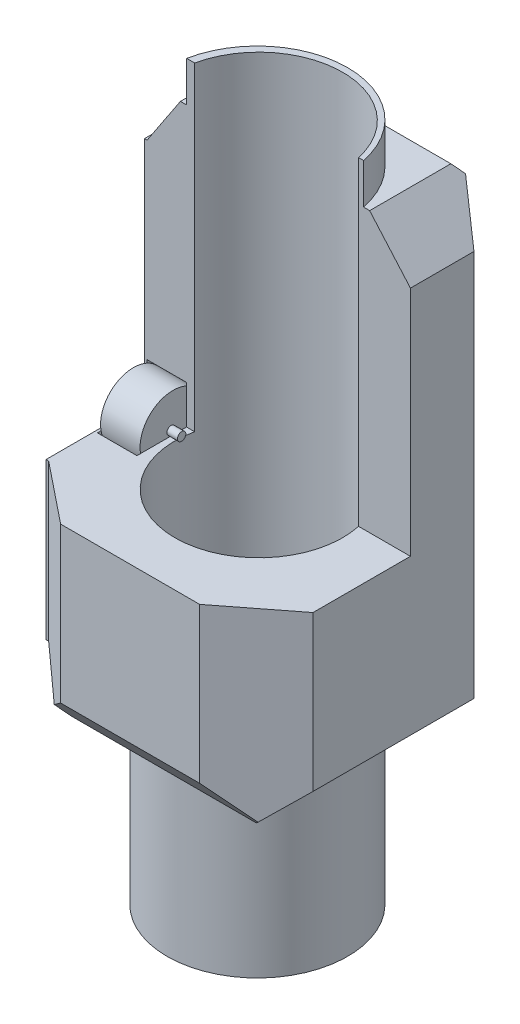
SolidWorks part; units mm, degrees
ref_plane "Front Plane" through (0, 0, 0) normal (0, 0, 1) x (1, 0, 0)
ref_plane "Top Plane" through (0, 0, 0) normal (0, 1, 0) x (1, 0, 0)
ref_plane "Right Plane" through (0, 0, 0) normal (1, 0, 0) x (0, 0, -1)
sketch "Sketch1" plane through (0, 0, 0) normal (0, 1, 0) x (1, 0, 0)
  line L1 (0, 0) -> (-100, 0)
  line L2 (0, 0) -> (0, 100)
  line L3 (0, 100) -> (-100, 100)
  line L4 (-100, 0) -> (-100, 100)
  dimension "D1" = 100
  dimension "D2" = 100
extrude "Boss-Extrude1" add sketch "Sketch1" along normal blind 180
sketch "Sketch2" plane through (0, 180, 0) normal (0, 1, 0) x (1, 0, 0)
  circle A0 centre (-51.3773, 49.0765) radius 34.2578
  point P2 (-49.1037, 52.2166)
  point P3 (-48.8771, 51.8469)
  point P4 (-51.3773, 49.0765)
extrude "Boss-Extrude2" add sketch "Sketch2" along normal mid plane 700
sketch "Sketch3" plane through (0, 0, 0) normal (1, 0, 0) x (0, 0, -1)
  line L1 (-18.5833, 361.0481) -> (133.4231, 361.0481)
  line L2 (-18.5833, 361.0481) -> (-18.5833, 643.5005)
  line L3 (-18.5833, 643.5005) -> (133.4231, 643.5005)
  line L4 (133.4231, 361.0481) -> (133.4231, 643.5005)
extrude "Cut-Extrude2" cut sketch "Sketch3" against normal blind 400
sketch "Sketch4" plane through (0, 0, 0) normal (1, 0, 0) x (0, 0, -1)
  line L0 (12.982, 0) -> (-8.9942, 25.8281)
  line L1 (-8.9942, 25.8281) -> (-18.5645, -15.2595)
  line L2 (-18.5645, -15.2595) -> (12.982, 0)
  line L3 (85.0725, -1.4481) -> (109.2376, 19.1131)
  line L4 (109.2376, 19.1131) -> (115.92, -3.2674)
  line L5 (115.92, -3.2674) -> (85.0725, -1.4481)
  line L6 (12.982, 180) -> (-8.9942, 148.5376)
  line L7 (-8.9942, 148.5376) -> (-15.4182, 193.2193)
  line L8 (-15.4182, 193.2193) -> (12.982, 180)
  line L9 (85.0725, 181.8543) -> (103.8412, 159.7959)
  line L10 (103.8412, 159.7959) -> (106.1325, 198.6474)
  line L11 (106.1325, 198.6474) -> (85.0725, 181.8543)
extrude "Cut-Extrude3" cut sketch "Sketch4" against normal blind 400
sketch "Sketch5" plane through (0, 0, 0) normal (0, 0, 1) x (1, 0, 0)
  line L0 (-85.6233, 0) -> (-106.3704, 21.4264)
  line L1 (-106.3704, 21.4264) -> (-122.2889, 3.2093)
  line L2 (-122.2889, 3.2093) -> (-93.5263, -19.8847)
  line L3 (-93.5263, -19.8847) -> (-85.6233, 0)
  line L4 (-15.695, 0) -> (0, 15.2574)
  line L5 (0, 15.2574) -> (12.1227, 15.2574)
  line L6 (12.1227, 15.2574) -> (10.5631, -19.8847)
  line L7 (10.5631, -19.8847) -> (-15.695, 0)
  line L8 (-87.1665, 180.2481) -> (-106.3704, 151.2911)
  line L9 (-106.3704, 151.2911) -> (-117.7055, 200.5011)
  line L10 (-117.7055, 200.5011) -> (-87.1665, 180.2481)
  line L11 (-15.695, 180.2481) -> (7.8338, 153.2796)
  line L12 (7.8338, 153.2796) -> (0, 193.9412)
  line L13 (0, 193.9412) -> (-15.695, 180.2481)
extrude "Cut-Extrude4" cut sketch "Sketch5" against normal blind 400
sketch "Sketch6" plane through (0, 180, 0) normal (0, 1, 0) x (1, 0, 0)
  line L1 (-112.387, 28.4004) -> (-64.2613, -10.2128)
  line L2 (-112.387, 28.4004) -> (-124.6497, -15.5119)
  line L3 (-124.6497, -15.5119) -> (-84.4064, -15.5119)
  line L4 (-64.2613, -10.2128) -> (-84.4064, -15.5119)
  line L5 (-97.0655, 135.8618) -> (-119.3755, 77.7927)
  line L6 (-97.0655, 135.8618) -> (-66.4287, 110.5752)
  line L7 (-66.4287, 110.5752) -> (-118.0433, 64.3476)
  line L8 (-119.3755, 77.7927) -> (-118.0433, 64.3476)
  line L9 (-24.6964, -21.8158) -> (11.0921, -8.9736)
  line L10 (-24.6964, -21.8158) -> (-38.5316, -11.1392)
  line L11 (-38.5316, -11.1392) -> (17.4283, 32.3938)
  line L12 (11.0921, -8.9736) -> (17.4283, 32.3938)
  line L13 (-17.4455, 140.8044) -> (35.4175, 107.2625)
  line L14 (-17.4455, 140.8044) -> (-31.7244, 103.6253)
  line L15 (-31.7244, 103.6253) -> (9.3055, 72.9964)
  line L16 (35.4175, 107.2625) -> (9.3055, 72.9964)
  point P4 (-17.4455, 140.8044)
  point P5 (-30.2763, 114.984)
  point P6 (35.4175, 107.2625)
  point P19 (-30.6265, 106.484)
  point P20 (-11.2095, 88.3109)
extrude "Cut-Extrude5" cut sketch "Sketch6" against normal blind 400
sketch "Sketch7" plane through (0, 0, 0) normal (0, 0, 1) x (1, 0, 0)
  line L1 (-146.2029, -210.0437) -> (13.9564, -210.0437)
  line L2 (-146.2029, -210.0437) -> (-146.2029, -62.6814)
  line L3 (-146.2029, -62.6814) -> (13.9564, -62.6814)
  line L4 (13.9564, -210.0437) -> (13.9564, -62.6814)
extrude "Cut-Extrude6" cut sketch "Sketch7" against normal blind 400
sketch "Sketch8" plane through (0, 0, 0) normal (0, 0, 1) x (1, 0, 0)
  line L1 (-127.1965, 251.4288) -> (20.1142, 251.4288)
  line L2 (-127.1965, 251.4288) -> (-127.1965, 413.4677)
  line L3 (-127.1965, 413.4677) -> (20.1142, 413.4677)
  line L4 (20.1142, 251.4288) -> (20.1142, 413.4677)
extrude "Cut-Extrude7" cut sketch "Sketch8" against normal blind 400
sketch "Sketch9" plane through (0, 251.4288, 0) normal (0, 1, 0) x (1, 0, 0)
  circle A0 centre (-50.809, 49.032) radius 31.8473
  point P2 (-50.6049, 49.6989)
  point P3 (-51.6378, 48.9774)
  point P4 (-50.809, 49.032)
extrude "Cut-Extrude8" cut sketch "Sketch9" against normal blind 400
sketch "Sketch10" plane through (-100, 0, 0) normal (-1, 0, 0) x (0, 0, 1)
  line L1 (-55.8114, 74.0839) -> (84.4096, 74.0839)
  line L2 (-55.8114, 74.0839) -> (-55.8114, 286.1174)
  line L3 (-55.8114, 286.1174) -> (84.4096, 286.1174)
  line L4 (84.4096, 74.0839) -> (84.4096, 286.1174)
extrude "Cut-Extrude9" cut sketch "Sketch10" against normal blind 400
sketch "Sketch11" plane through (-100, 0, 0) normal (-1, 0, 0) x (0, 0, 1)
  circle A0 centre (-50.4133, 76.2646) radius 13.6031
  point P2 (-50.4133, 76.2646)
extrude "Cut-Extrude11" cut sketch "Sketch11" against normal blind 15
sketch "Sketch12" plane through (-85, 0, 0) normal (-1, 0, 0) x (0, 0, 1)
  circle A0 centre (-50.6588, 76.2225) radius 12.4954
  point P2 (-51.6147, 75.8831)
  point P3 (-50.6588, 76.2225)
extrude "Boss-Extrude3" add sketch "Sketch12" along normal blind 15
sketch "Sketch13" plane through (-85, 0, 0) normal (1, 0, 0) x (0, 0, -1)
  circle A0 centre (49.9452, 75.9448) radius 1.5949
extrude "Boss-Extrude4" add sketch "Sketch13" along normal blind 4
sketch "Sketch14" plane through (-100, 0, 0) normal (-1, 0, 0) x (0, 0, 1)
  line L1 (-115.7243, 195.3259) -> (-14.9757, 195.3259)
  line L2 (-115.7243, 195.3259) -> (-115.7243, 305.8809)
  line L3 (-115.7243, 305.8809) -> (-14.9757, 305.8809)
  line L4 (-14.9757, 195.3259) -> (-14.9757, 305.8809)
extrude "Cut-Extrude13" cut sketch "Sketch14" against normal blind 400
sketch "Sketch15" plane through (-100, 0, 0) normal (-1, 0, 0) x (0, 0, 1)
  line L0 (-18.4618, 14.8474) -> (-80.5077, 14.8474)
  line L1 (-80.5077, 14.8474) -> (-80.5077, 160.8968)
  line L2 (-80.5077, 160.8968) -> (-55.8114, 160.8968)
  line L3 (-55.8114, 160.8968) -> (-55.8114, 74.0839)
  line L4 (-55.8114, 74.0839) -> (-18.4618, 74.0839)
  line L5 (-18.4618, 74.0839) -> (-18.4618, 14.8474)
extrude "Boss-Extrude5" add sketch "Sketch15" along normal blind 1
sketch "Sketch16" plane through (-101, 0, 0) normal (-1, 0, 0) x (0, 0, 1)
  line L1 (-69.1316, 29.9073) -> (-27.023, 29.9073)
  line L2 (-69.1316, 29.9073) -> (-69.1316, 60.3656)
  line L3 (-69.1316, 60.3656) -> (-27.023, 60.3656)
  line L4 (-27.023, 29.9073) -> (-27.023, 60.3656)
extrude "Boss-Extrude6" add sketch "Sketch16" along normal blind 5
sketch "Sketch17" plane through (-101, 0, 0) normal (-1, 0, 0) x (0, 0, 1)
  line L1 (-76.3814, 119.2079) -> (-57.7119, 119.2079)
  line L2 (-76.3814, 119.2079) -> (-76.3814, 141.6106)
  line L3 (-76.3814, 141.6106) -> (-57.7119, 141.6106)
  line L4 (-57.7119, 119.2079) -> (-57.7119, 141.6106)
extrude "Boss-Extrude7" add sketch "Sketch17" along normal blind 1
sketch "Sketch18" plane through (-102, 0, 0) normal (-1, 0, 0) x (0, 0, 1)
  line L1 (-74.0789, 127.628) -> (-69.1713, 127.628)
  line L2 (-74.0789, 127.628) -> (-74.0789, 132.7988)
  line L3 (-74.0789, 132.7988) -> (-69.1713, 132.7988)
  line L4 (-69.1713, 127.628) -> (-69.1713, 132.7988)
  line L5 (-60.3069, 127.1415) -> (-64.2884, 127.1415)
  line L6 (-60.3069, 127.1415) -> (-60.3069, 132.5929)
  line L7 (-60.3069, 132.5929) -> (-64.2884, 132.5929)
  line L8 (-64.2884, 127.1415) -> (-64.2884, 132.5929)
extrude "Boss-Extrude8" add sketch "Sketch18" along normal blind 1
sketch "Sketch19" plane through (-102, 0, 0) normal (-1, 0, 0) x (0, 0, 1)
  line L0 (-66.9765, 134.8688) -> (-73.7929, 134.8688)
  line L1 (-73.7929, 134.8688) -> (-73.7929, 134.1083)
  line L2 (-73.7929, 134.1083) -> (-74.5719, 134.1083)
  line L3 (-74.5719, 134.1083) -> (-74.5719, 140.5127)
  line L4 (-74.5719, 140.5127) -> (-73.7929, 140.5127)
  line L5 (-73.7929, 140.5127) -> (-72.166, 140.5127)
  line L6 (-66.9765, 134.8688) -> (-66.9765, 135.4972)
  line L7 (-66.9765, 135.4972) -> (-73.7929, 135.4233)
  line L8 (-73.7929, 135.4233) -> (-73.7929, 139.5456)
  line L9 (-73.7929, 139.5456) -> (-72.9212, 139.5456)
  line L10 (-72.9212, 139.5456) -> (-72.9212, 136.6931)
  line L11 (-72.166, 140.5127) -> (-72.2334, 137.4219)
  line L12 (-72.9212, 136.6931) -> (-70.7839, 136.6931)
  line L13 (-72.2334, 137.4219) -> (-71.4846, 137.4219)
  line L14 (-71.4846, 137.4219) -> (-71.4109, 140.5127)
  line L15 (-71.4109, 140.5127) -> (-69.1583, 140.5049)
  line L16 (-70.7839, 136.6931) -> (-70.7097, 139.9027)
  line L17 (-70.7097, 139.9027) -> (-70.0087, 139.9027)
  line L18 (-69.1583, 140.5049) -> (-69.1583, 137.4219)
  line L19 (-70.0087, 139.9027) -> (-70.0087, 136.6677)
  line L20 (-70.0087, 136.6677) -> (-67.49, 136.6677)
  line L21 (-69.1583, 137.4219) -> (-68.2217, 137.4219)
  line L22 (-67.49, 136.6677) -> (-67.49, 139.9027)
  line L23 (-67.49, 139.9027) -> (-66.3346, 139.9027)
  line L24 (-66.3346, 139.9027) -> (-66.3346, 136.6677)
  line L25 (-68.2217, 137.4219) -> (-68.2217, 140.5679)
  line L26 (-68.2217, 140.5679) -> (-65.4269, 140.5679)
  line L27 (-65.4269, 140.5679) -> (-65.5152, 137.4462)
  line L28 (-66.3346, 136.6677) -> (-64.0048, 136.6677)
  line L29 (-64.0048, 136.6677) -> (-64.0048, 139.9797)
  line L30 (-64.0048, 139.9797) -> (-63.0901, 139.9797)
  line L31 (-63.0901, 139.9797) -> (-63.0901, 136.6677)
  line L32 (-63.0901, 136.6677) -> (-60.6958, 136.6677)
  line L33 (-60.6958, 136.6677) -> (-60.6958, 139.9841)
  line L34 (-60.6958, 139.9841) -> (-59.6983, 139.9949)
  line L35 (-65.5152, 137.4462) -> (-64.7141, 137.4462)
  line L36 (-64.7141, 137.4462) -> (-64.7141, 140.5679)
  line L37 (-64.7141, 140.5679) -> (-62.4109, 140.5679)
  line L38 (-62.4109, 140.5679) -> (-62.4109, 137.2101)
  line L39 (-62.4109, 137.2101) -> (-61.4035, 137.2101)
  line L40 (-61.4035, 137.2101) -> (-61.4035, 140.6311)
  line L41 (-61.4035, 140.6311) -> (-58.89, 140.6311)
  line L42 (-58.89, 140.6311) -> (-58.89, 136.5955)
  line L43 (-58.89, 136.5955) -> (-59.6983, 136.5955)
  line L44 (-59.6983, 136.5955) -> (-59.6983, 139.9949)
  point P27 (-64.7141, 140.5679)
extrude "Boss-Extrude9" add sketch "Sketch19" along normal blind 1
